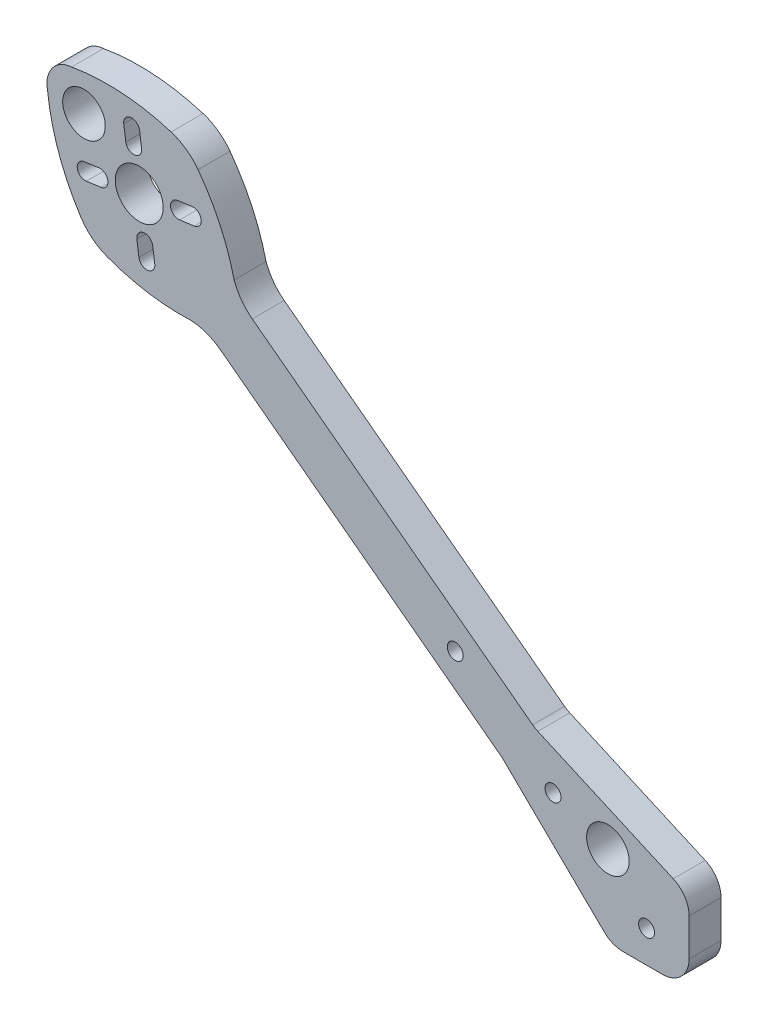
SolidWorks part; units mm, degrees
material "Thornel Mat VMA"
ref_plane "Alzado" through (0, 0, 0) normal (0, 0, 1) x (1, 0, 0)
ref_plane "Planta" through (0, 0, 0) normal (0, 1, 0) x (1, 0, 0)
ref_plane "Vista lateral" through (0, 0, 0) normal (1, 0, 0) x (0, 0, -1)
sketch "Croquis1" plane through (0, 0, 0) normal (0, 0, 1) x (1, 0, 0)
  line L0 (-190.6259, 103.2863) -> (-181.6394, 96.5144) construction
  line L1 (-181.6394, 96.5144) -> (-187.6575, 88.5281) construction
  line L2 (-187.6575, 88.5281) -> (-196.3333, 95.0657) construction
  line L3 (-161.2306, 79.8747) -> (-161.2306, 86.8707)
  line L4 (-164.2059, 91.4424) -> (-189.6416, 102.7078)
  line L5 (-161.2306, 74.8747) -> (-264.512, 152.7028) construction
  line L6 (-166.2306, 74.8747) -> (-173.6595, 74.8747)
  line L7 (-177.1564, 76.3009) -> (-196.1029, 94.8403)
  line L8 (-264.512, 152.7028) -> (-274.8943, 160.5264) construction
  line L9 (-264.512, 152.7028) -> (-266.1473, 164.3384) construction
  line L11 (-267.4239, 162.6443) -> (-267.0343, 159.8715)
  line L15 (-264.0635, 160.289) -> (-264.4531, 163.0618)
  line L19 (-267.6327, 164.1297) -> (-267.4239, 162.6443) construction
  line L20 (-267.4239, 162.6443) -> (-264.4531, 163.0618) construction
  line L21 (-266.8255, 158.3861) -> (-267.0343, 159.8715) construction
  line L22 (-267.0343, 159.8715) -> (-264.0635, 160.289) construction
  line L23 (-254.5705, 155.6147) -> (-257.3433, 155.225)
  line L24 (-256.9258, 152.2542) -> (-254.153, 152.6439)
  line L25 (-261.6001, 142.7613) -> (-261.9898, 145.534)
  line L26 (-264.9606, 145.1165) -> (-264.5709, 142.3438)
  line L27 (-274.4535, 149.7908) -> (-271.6808, 150.1805)
  line L28 (-272.0983, 153.1513) -> (-274.871, 152.7616)
  line L29 (-196.5907, 95.2597) -> (-249.3006, 134.9795)
  line L30 (-264.512, 152.7028) -> (-273.5392, 140.7232) construction
  line L31 (-263.0855, 142.5525) -> (-262.8767, 141.0671) construction
  line L32 (-274.8943, 160.5264) -> (-282.8806, 166.5445) construction
  line L33 (-262.8767, 141.0671) -> (-262.3693, 137.4568) construction
  line L34 (-274.6623, 151.2762) -> (-276.1477, 151.0675) construction
  line L35 (-276.1477, 151.0675) -> (-279.6136, 150.5804) construction
  line L36 (-190.3151, 103.0521) -> (-243.2825, 142.9659)
  line L37 (-200.0123, 198.245) -> (-200.0123, 110.3594) construction
  circle A0 centre (-205.1556, 107.9745) radius 1.5
  circle A1 centre (-186.7909, 94.1357) radius 1.5
  circle A2 centre (-176.4806, 90.1247) radius 4
  circle A3 centre (-169.217, 80.8928) radius 1.5
  circle A5 centre (-161.2306, 74.8747) radius 10 construction
  circle A6 centre (-161.2306, 74.8747) radius 129.3223 construction
  circle A7 centre (-264.512, 152.7028) radius 4.5
  circle A8 centre (-274.8943, 160.5264) radius 4
  arc A9 (-267.4239, 162.6443) -> (-264.4531, 163.0618) centre (-265.9385, 162.853) cw
  arc A10 (-267.0343, 159.8715) -> (-264.0635, 160.289) centre (-265.5489, 160.0803) ccw
  arc A11 (-254.5705, 155.6147) -> (-254.153, 152.6439) centre (-254.3618, 154.1293) cw
  arc A12 (-257.3433, 155.225) -> (-256.9258, 152.2542) centre (-257.1345, 153.7396) ccw
  arc A13 (-261.6001, 142.7613) -> (-264.5709, 142.3438) centre (-263.0855, 142.5525) cw
  arc A14 (-261.9898, 145.534) -> (-264.9606, 145.1165) centre (-263.4752, 145.3253) ccw
  arc A15 (-274.4535, 149.7908) -> (-274.871, 152.7616) centre (-274.6623, 151.2762) cw
  arc A16 (-271.6808, 150.1805) -> (-272.0983, 153.1513) centre (-271.8895, 151.6659) ccw
  arc A17 (-249.3006, 134.9795) -> (-254.6905, 136.9734) centre (-255.3188, 126.9931) ccw
  arc A18 (-254.6905, 136.9734) -> (-270.5641, 139.4702) centre (-256.5386, 176.9307) cw
  arc A19 (-277.233, 166.9825) -> (-281.7449, 160.995) centre (-276.8465, 161.9974) ccw
  arc A20 (-281.7449, 160.995) -> (-275.418, 143.3485) centre (-241.9768, 165.2959) ccw
  arc A21 (-270.5641, 139.4702) -> (-275.418, 143.3485) centre (-267.0577, 148.8353) cw
  arc A22 (-243.2825, 142.9659) -> (-246.6848, 147.5973) centre (-237.2643, 150.9522) cw
  arc A23 (-246.6848, 147.5973) -> (-253.4602, 162.1678) centre (-285.6036, 138.3601) ccw
  arc A24 (-253.4602, 162.1678) -> (-258.5262, 165.7647) centre (-261.4961, 156.2159) ccw
  arc A25 (-277.233, 166.9825) -> (-258.5262, 165.7647) centre (-270.4057, 127.5694) cw
  arc A26 (-173.6595, 74.8747) -> (-177.1564, 76.3009) centre (-173.6595, 79.8747) cw
  arc A27 (-161.2306, 79.8747) -> (-166.2306, 74.8747) centre (-166.2306, 79.8747) cw
  arc A28 (-161.2306, 86.8707) -> (-164.2059, 91.4424) centre (-166.2306, 86.8707) ccw
  arc A29 (-190.6259, 103.2863) -> (-189.6416, 102.7078) centre (-187.6168, 107.2794) ccw
  arc A30 (-196.1029, 94.8403) -> (-196.5907, 95.2597) centre (-199.5998, 91.2665) ccw
  circle A32 centre (-264.512, 152.7028) radius 64 construction
  point P52 (-264.512, 152.7028)
  point P60 (-276.1968, 155.2472)
  point P80 (-175.6988, 74.8747)
  point P86 (-161.2306, 90.1247)
  dimension "D1" = 45
  dimension "D17" = 8
  dimension "D18" = 9
  dimension "D21" = 10
  dimension "D23" = 40
  dimension "D24" = 5
  dimension "D25" = 10
  dimension "D26" = 5
  dimension "D10" = 8
  dimension "D35" = 8.4146
  dimension "D39" = 11.7531
  dimension "D2" = 11.75
  dimension "D3" = 3
  dimension "D4" = 4
  dimension "D5" = 1.5
  dimension "D6" = 10
  dimension "D7" = 32.0049
  dimension "D8" = 21.5668
  dimension "D9" = 3.0015
  dimension "D11" = 66
  dimension "D12" = 22.9951
  dimension "D13" = 14.4682
  dimension "D14" = 15.25
  dimension "D15" = 100
  dimension "D16" = 13
  dimension "D19" = 10
  dimension "D20" = 15
  dimension "D22" = 5
  dimension "D27" = 18.5439
  dimension "D28" = 36.4193
  dimension "D29" = 14.4957
  dimension "D30" = 13.3026
  dimension "D31" = 15.8736
  dimension "D32" = 14.5704
  dimension "D33" = 3.8783
  dimension "D34" = 17.6465
  dimension "D36" = 10.2091
  dimension "D37" = 0.6434
  dimension "D38" = 9.5875
extrude "Saliente-Extruir1" add sketch "Croquis1" along normal blind 6
